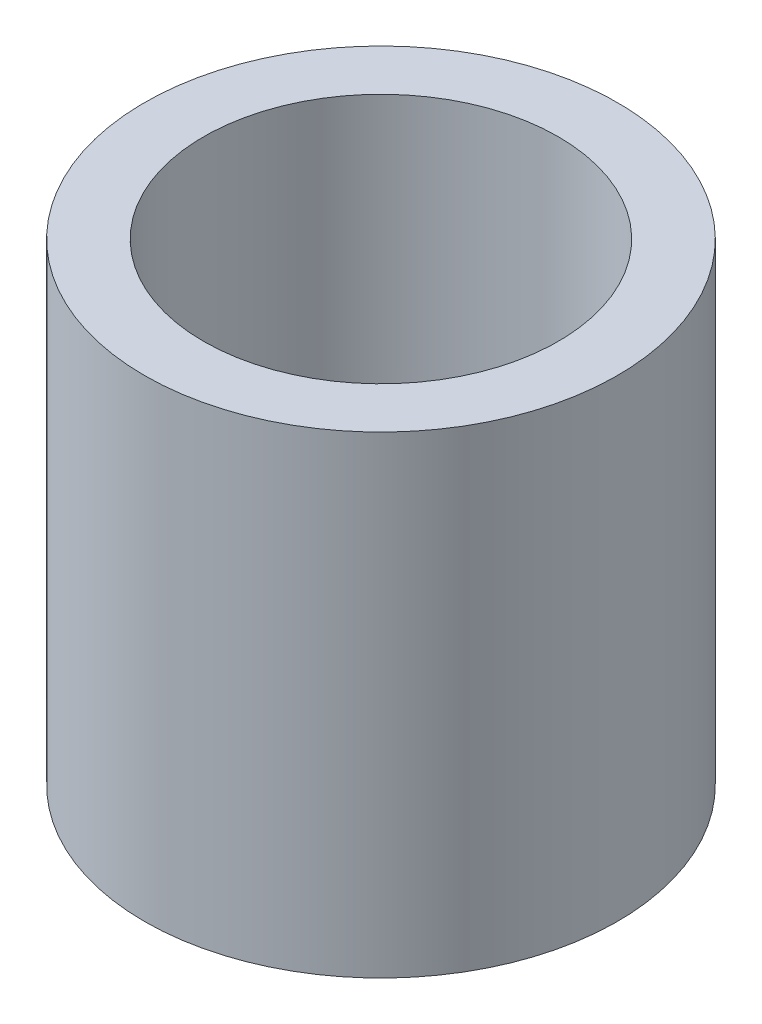
SolidWorks part; units mm, degrees
ref_plane "Front Plane" through (0, 0, 0) normal (0, 0, 1) x (1, 0, 0)
ref_plane "Top Plane" through (0, 0, 0) normal (0, 1, 0) x (1, 0, 0)
ref_plane "Right Plane" through (0, 0, 0) normal (1, 0, 0) x (0, 0, -1)
sketch "Sketch1" plane through (0, 0, 0) normal (0, 1, 0) x (1, 0, 0)
  circle A0 centre (0, 0) radius 2
  circle A1 centre (0, 0) radius 1.5
  dimension "D1" = 4
  dimension "D2" = 3
extrude "Boss-Extrude1" add sketch "Sketch1" along normal mid plane 4
